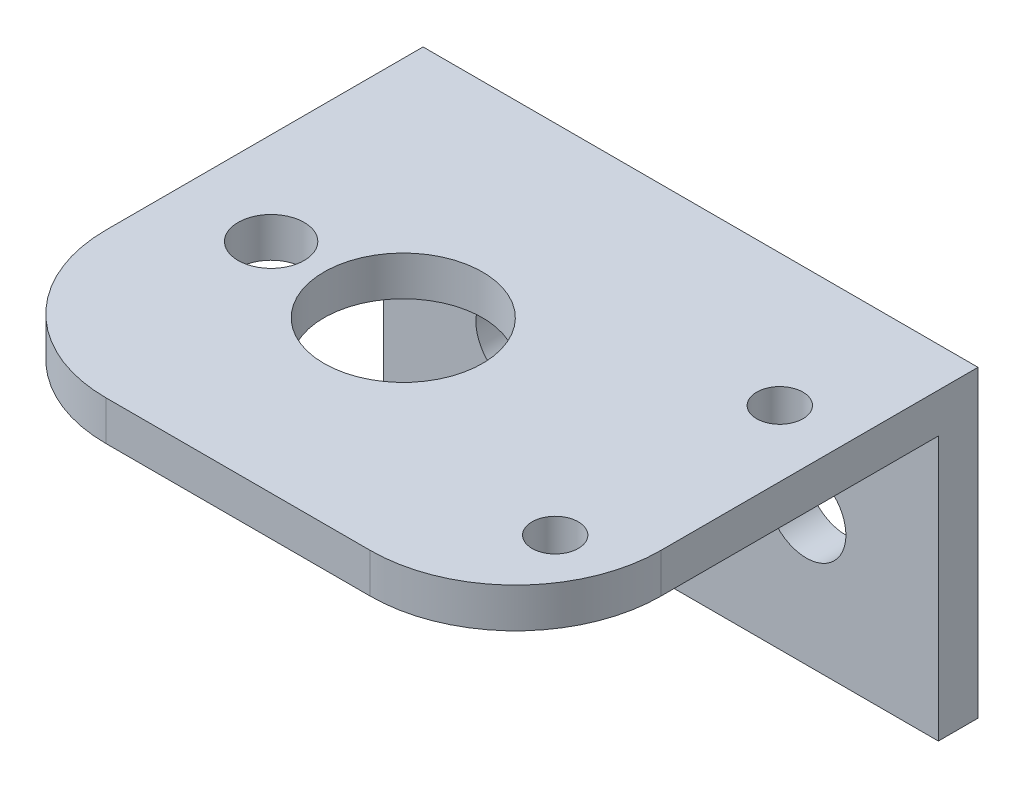
SolidWorks part; units mm, degrees
ref_plane "Front Plane" through (0, 0, 0) normal (0, 0, 1) x (1, 0, 0)
ref_plane "Top Plane" through (0, 0, 0) normal (0, 1, 0) x (1, 0, 0)
ref_plane "Right Plane" through (0, 0, 0) normal (1, 0, 0) x (0, 0, -1)
sketch "Sketch1" plane through (0, 0, 0) normal (0, 1, 0) x (1, 0, 0)
  line L0 (5, -10) -> (5, -27) construction
  line L1 (0, 0) -> (42, 0)
  line L2 (0, 0) -> (0, -35)
  line L3 (0, -35) -> (42, -35)
  line L4 (42, 0) -> (42, -35)
  line L5 (5, -18.5) -> (78.5425, -18.5) construction
  line L6 (76.0507, 18.6222) -> (80.4984, -47.6371) construction
  circle A0 centre (5, -10) radius 1.75
  circle A1 centre (5, -27) radius 1.75
  circle A2 centre (25, -18.5) radius 6
  circle A3 centre (35, -18.5) radius 2.5
  dimension "D6" = 3.5
  dimension "D7" = 3.5
  dimension "D10" = 12
  dimension "D11" = 5
  dimension "D1" = 42
  dimension "D2" = 35
  dimension "D3" = 17
  dimension "D4" = 10
  dimension "D5" = 5
  dimension "D8" = 20
  dimension "D9" = 30
extrude "Boss-Extrude1" add sketch "Sketch1" along normal blind 3
sketch "Sketch2" plane through (0, 0, 0) normal (0, -1, 0) x (1, 0, 0)
  line L0 (42, 35) -> (42, 0) construction
  line L1 (0, 0) -> (42, 0)
  line L2 (0, 0) -> (0, 3)
  line L3 (0, 3) -> (42, 3)
  line L4 (42, 0) -> (42, 3)
  dimension "D1" = 3
extrude "Boss-Extrude2" add sketch "Sketch2" along normal blind 20
sketch "Sketch3" plane through (0, 0, 0) normal (0, 0, -1) x (-1, 0, 0)
  line L0 (-42, 3) -> (-42, -20) construction
  line L1 (0, 3) -> (0, -20) construction
  line L2 (-42, 0) -> (0, 0) construction
  line L3 (-42, 0) -> (0, 0) construction
  circle A0 centre (-32, -10) radius 3
  circle A1 centre (-10, -10) radius 3
  dimension "D1" = 6
  dimension "D2" = 6
  dimension "D3" = 10
  dimension "D4" = 10
  dimension "D5" = 10
  dimension "D6" = 10
extrude "Cut-Extrude1" cut sketch "Sketch3" against normal blind 20
fillet "Fillet1" radius 11 2 edges at (42, 1.5, 35) (0, 1.5, 35)
ref_plane "Plane1" through (0, 0, 0) normal (-1, 0, 0) x (0, 0, 1)
mirror "Mirror2" about plane through (0, 3, 0) normal (1, 0, 0) of "Fillet1", "Cut-Extrude1", "Boss-Extrude2", "Boss-Extrude1"
sketch "Sketch4" plane through (0, 0, 0) normal (-1, 0, 0) x (0, 0, 1)
  line L1 (-14.5909, 14.4881) -> (47.4718, 14.4881)
  line L2 (-14.5909, 14.4881) -> (-14.5909, -32.9836)
  line L3 (-14.5909, -32.9836) -> (47.4718, -32.9836)
  line L4 (47.4718, 14.4881) -> (47.4718, -32.9836)
extrude "Cut-Extrude2" cut sketch "Sketch4" against normal blind 70
